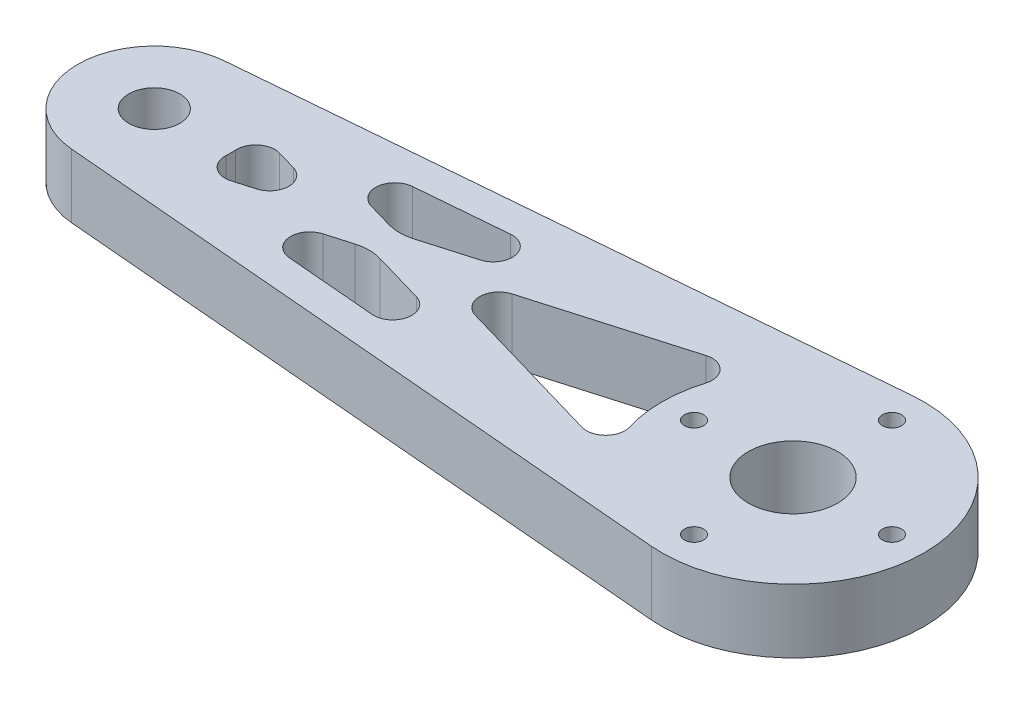
SolidWorks part; units mm, degrees
material "1060 Alloy"
ref_plane "Front Plane" through (0, 0, 0) normal (0, 0, 1) x (1, 0, 0)
ref_plane "Top Plane" through (0, 0, 0) normal (0, 1, 0) x (1, 0, 0)
ref_plane "Right Plane" through (0, 0, 0) normal (1, 0, 0) x (0, 0, -1)
sketch "Sketch1" plane through (0, 0, 0) normal (0, 1, 0) x (1, 0, 0)
  line L0 (-1.7425, -20.4258) -> (-101.02, -11.9566)
  line L1 (-1.7425, 20.4258) -> (-101.02, 11.9566)
  line L2 (-90.8835, 7.8031) -> (-14.6854, 14.3035) construction
  line L3 (-90.8835, -7.8031) -> (-14.6854, -14.3035) construction
  line L5 (-100, 0) -> (0, 0) construction
  line L6 (-90.8835, -7.8031) -> (-14.6854, 14.3035) construction
  line L7 (-14.6854, -14.3035) -> (-90.8835, 7.8031) construction
  line L8 (-84.191, -3.779) -> (-81.0962, -2.8812)
  line L9 (-69.8322, -3.7782) -> (-65.9377, -2.6483)
  line L10 (-62.0369, -2.6483) -> (-53.9695, -4.9888)
  line L11 (-46.8783, -2.8812) -> (-23.32, -9.7159)
  line L12 (-46.8783, 2.8812) -> (-23.32, 9.7159)
  line L13 (-62.0369, 2.6483) -> (-53.9695, 4.9888)
  line L14 (-65.9377, 2.6483) -> (-69.8322, 3.7782)
  line L15 (-81.0962, 2.8812) -> (-84.191, 3.779)
  line L16 (-69.2514, -9.6486) -> (-55.0604, -10.8592)
  line L17 (-55.0604, 10.8592) -> (-69.2514, 9.6486)
  line L18 (-100, 0) -> (-101.02, 11.9566) construction
  line L19 (-100, 0) -> (-101.02, -11.9566) construction
  line L20 (-100, 0) -> (-88, 0) construction
  arc A1 (-101.02, 11.9566) -> (-101.02, -11.9566) centre (-100, 0) ccw
  arc A2 (-1.7425, 20.4258) -> (-1.7425, -20.4258) centre (0, 0) cw
  circle A3 centre (0, 0) radius 7
  circle A4 centre (-100, 0) radius 4
  arc A6 (-14.6854, 14.3035) -> (-14.6854, -14.3035) centre (0, 0) ccw construction
  arc A13 (-90.8835, -7.8031) -> (-90.8835, 7.8031) centre (-100, 0) ccw construction
  arc A14 (-88.0215, -0.7183) -> (-88.0215, 0.7183) centre (-100, 0) ccw
  arc A15 (-19.6138, -5.9622) -> (-19.6138, 5.9622) centre (0, 0) cw
  arc A16 (-62.0369, -2.6483) -> (-65.9377, -2.6483) centre (-63.9873, -9.3711) ccw
  arc A17 (-65.9377, 2.6483) -> (-62.0369, 2.6483) centre (-63.9873, 9.3711) ccw
  arc A18 (-53.9695, 4.9888) -> (-55.0604, 10.8592) centre (-54.8054, 7.87) ccw
  arc A19 (-69.8322, 3.7782) -> (-69.2514, 9.6486) centre (-68.9964, 6.6594) cw
  arc A20 (-69.8322, -3.7782) -> (-69.2514, -9.6486) centre (-68.9964, -6.6594) ccw
  arc A21 (-19.6138, 5.9622) -> (-23.32, 9.7159) centre (-22.4841, 6.8347) ccw
  arc A22 (-23.32, -9.7159) -> (-19.6138, -5.9622) centre (-22.4841, -6.8347) ccw
  arc A23 (-46.8783, 2.8812) -> (-46.8783, -2.8812) centre (-46.0424, 0) ccw
  arc A24 (-81.0962, -2.8812) -> (-81.0962, 2.8812) centre (-81.9321, 0) ccw
  arc A25 (-88.0215, 0.7183) -> (-84.191, 3.779) centre (-85.0269, 0.8979) cw
  arc A26 (-84.191, -3.779) -> (-88.0215, -0.7183) centre (-85.0269, -0.8979) cw
  circle A27 centre (-100, 0) radius 8 construction
  circle A28 centre (0, 0) radius 15.5 construction
  arc A29 (-53.9695, -4.9888) -> (-55.0604, -10.8592) centre (-54.8054, -7.87) cw
  point P31 (-24.8531, 13.4361)
  point P34 (-85.3366, 8.2763)
  point P37 (-85.3366, -8.2763)
  point P41 (-16.9213, 11.5723)
  point P44 (-16.9213, -11.5723)
  point P51 (-89.2009, 5.2325)
  point P54 (-89.2009, -5.2325)
  point P58 (-88, 0)
  point P63 (-24.8531, -13.4361)
  dimension "D1" = 100
  dimension "D6" = 8
  dimension "D7" = 14
  dimension "D10" = 3
  dimension "D11" = 20.5
  dimension "D12" = 2
  dimension "D13" = 2
  dimension "D14" = 2
  dimension "D16" = 7
  dimension "D17" = 3
  dimension "D18" = 3
  dimension "D19" = 16
  dimension "D20" = 31
  dimension "D3" = 12
  dimension "D4" = 20.5
  dimension "D5" = 20.5
  dimension "D8" = 5
  dimension "D9" = 5
  dimension "D15" = 2
extrude "Boss-Extrude1" add sketch "Sketch1" along normal blind 10
sketch "Sketch2" plane through (0, 10, 0) normal (0, 1, 0) x (1, 0, 0)
  line L0 (0, 0) -> (-100, 0) construction
  line L1 (0, 0) -> (-15.5, 0) construction
  line L2 (15.5, 0) -> (-15.5, 0) construction
  circle A0 centre (-15.5, 0) radius 1.5
  circle A1 centre (0, 15.5) radius 1.5
  circle A2 centre (15.5, 0) radius 1.5
  circle A3 centre (0, -15.5) radius 1.5
  dimension "D1" = 3
  dimension "D2" = 15.5
  dimension "D4" = 15.5
  dimension "D3" = 4
extrude "Cut-Extrude1" cut sketch "Sketch2" against normal blind 10
